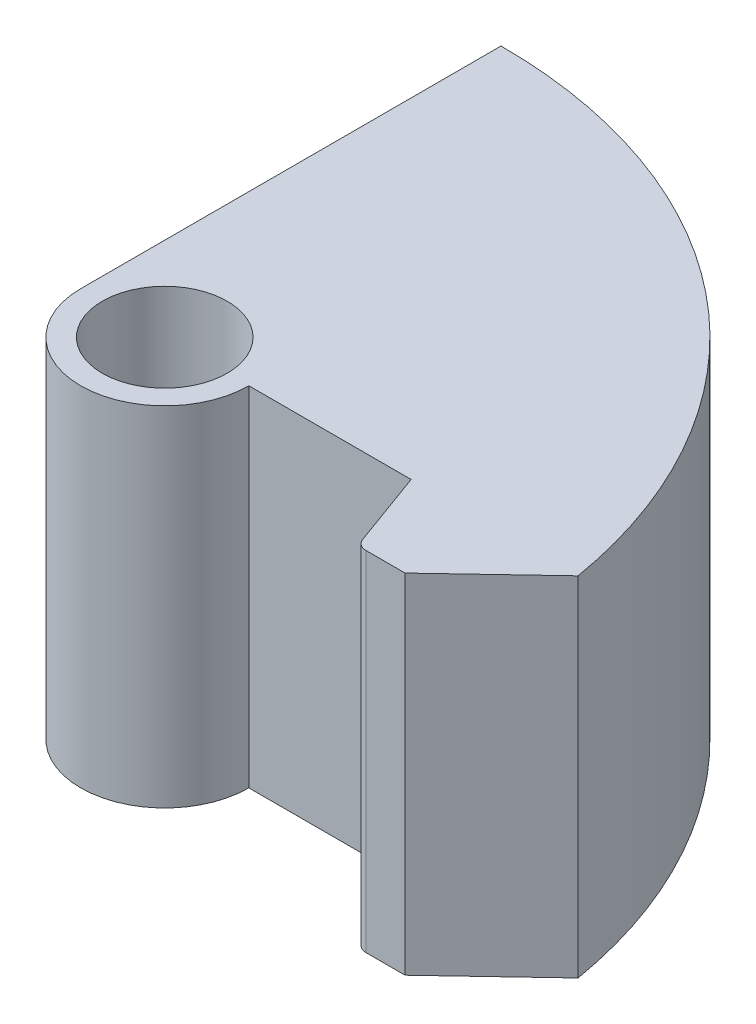
SolidWorks part; units mm, degrees
material "PLA"
ref_plane "Front Plane" through (0, 0, 0) normal (0, 0, 1) x (1, 0, 0)
ref_plane "Top Plane" through (0, 0, 0) normal (0, 1, 0) x (1, 0, 0)
ref_plane "Right Plane" through (0, 0, 0) normal (1, 0, 0) x (0, 0, -1)
sketch "Sketch2" plane through (0, 0, 0) normal (0, 1, 0) x (1, 0, 0)
  line L0 (-3.5, 0) -> (-3.5, -3.5)
  line L1 (-3.5, -3.5) -> (0, -3.5)
  line L2 (-3.5, -3.5) -> (17.5, -3.5)
  line L3 (-3.5, -3.5) -> (-3.5, 17.5)
  line L4 (3.5, 0) -> (17.2063, 0)
  circle A0 centre (0, 0) radius 2.6
  circle A1 centre (0, 0) radius 3.5
  circle A2 centre (-3.5, -3.5) radius 21
  dimension "D1" = 5.2
  dimension "D2" = 7
  dimension "D4" = 42
  dimension "D3" = 3.5
extrude "Boss-Extrude1" add sketch "Sketch2" along normal blind 14.6 contours L4 A2 L3 A1 | A1 A0
sketch "Sketch4" plane through (0, 14.6, 0) normal (0, 1, 0) x (1, 0, 0)
  line L1 (-8.6615, 22.387) -> (30.5932, 22.387)
  line L2 (-8.6615, 22.387) -> (-8.6615, -12.7916)
  line L3 (-8.6615, -12.7916) -> (30.5932, -12.7916)
  line L4 (30.5932, 22.387) -> (30.5932, -12.7916)
extrude "Cut-Extrude1" cut sketch "Sketch4" against normal blind 0.1
sketch "Sketch7" plane through (0, 0, 0) normal (0, -1, 0) x (-1, 0, 0)
  line L1 (-3.5, 0) -> (-17.2063, 0) construction
  line L2 (-11.4112, -3.171) -> (-10.257, 0)
  line L3 (-10.257, 0) -> (-13.505, 0)
  line L4 (-13.505, 0) -> (-17.2063, 0)
  line L5 (-11.881, -3.5) -> (-13.505, -3.5)
  line L7 (-17.2063, 0) -> (-13.505, -3.5)
  arc A0 (-11.4112, -3.171) -> (-11.881, -3.5) centre (-11.881, -3) cw
  arc A1 (3.5, 17.5) -> (-17.2063, 0) centre (3.5, -3.5) ccw construction
  dimension "D1" = 0.5
  dimension "D2" = 3
  dimension "D3" = 70
extrude "Boss-Extrude5" add sketch "Sketch7" against normal up to surface (14.5 mm away) up to face at (0, 14.5, 2.6)
